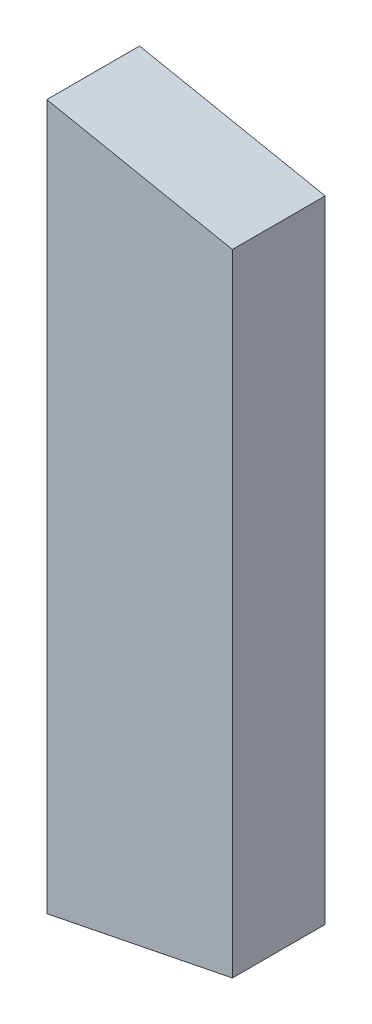
SolidWorks part; units mm, degrees
ref_plane "Front Plane" through (0, 0, 0) normal (0, 0, 1) x (1, 0, 0)
ref_plane "Top Plane" through (0, 0, 0) normal (0, 1, 0) x (1, 0, 0)
ref_plane "Right Plane" through (0, 0, 0) normal (1, 0, 0) x (0, 0, -1)
sketch "Sketch1" plane through (0, 0, 0) normal (0, 0, 1) x (1, 0, 0)
  line L1 (-5, -19) -> (5, -19)
  line L2 (-5, -19) -> (-5, 19)
  line L3 (-5, 19) -> (5, 19)
  line L4 (5, -19) -> (5, 19)
  line L5 (-5, -19) -> (5, 19) construction
  line L6 (-5, 19) -> (5, -19) construction
  point P0 (0, 0)
  dimension "D1" = 38
  dimension "D2" = 10
extrude "Boss-Extrude1" add sketch "Sketch1" along normal blind 5
sketch "Sketch2" plane through (0, 0, 5) normal (0, 0, 1) x (1, 0, 0)
  line L0 (-5, 19) -> (10, 16.0028)
  line L1 (10, 16.0028) -> (10, -16.0028)
  line L2 (10, -16.0028) -> (-5, -19)
  line L3 (-5, -19) -> (-5, -28.7066)
  line L4 (-5, -28.7066) -> (20.4818, -28.7066)
  line L5 (20.4818, -28.7066) -> (20.4818, 22.2934)
  line L6 (20.4818, 22.2934) -> (-5.0345, 22.2934)
  line L7 (-5.0345, 22.2934) -> (-5, 19)
  line L9 (5, -19) -> (5, 19) construction
  point P14 (10, 0)
  dimension "D1" = 51
  dimension "D2" = 5
  dimension "D3" = 51
extrude "Cut-Extrude1" cut sketch "Sketch2" against normal blind 27
